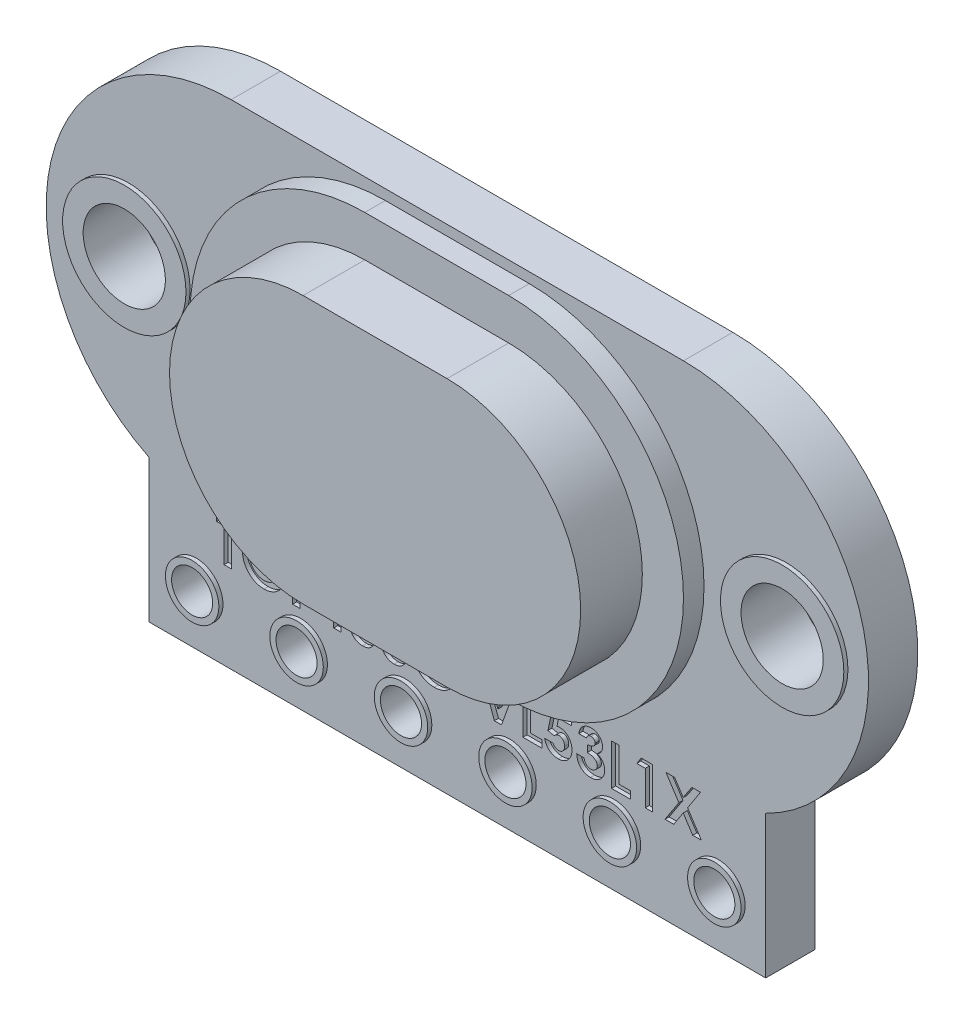
SolidWorks part; units mm, degrees
ref_plane "Plan de face" through (0, 0, 0) normal (0, 0, 1) x (1, 0, 0)
ref_plane "Plan de dessus" through (0, 0, 0) normal (0, 1, 0) x (1, 0, 0)
ref_plane "Plan de droite" through (0, 0, 0) normal (1, 0, 0) x (0, 0, -1)
sketch "Esquisse1" plane through (0, 0, 0) normal (0, 0, 1) x (1, 0, 0)
  line L0 (-7.5, -4.0311) -> (-7.5, -7.5)
  line L1 (0, 19.431) -> (0, -15.0057) construction
  line L2 (-5.5, 0) -> (5.5, 0) construction
  line L5 (-7.5, -7.5) -> (7.5, -7.5)
  line L6 (7.5, -4.0311) -> (7.5, -7.5)
  line L7 (-6.35, -6.23) -> (-3.81, -6.23) construction
  line L8 (-5.5, 4.5) -> (5.5, 4.5)
  circle A2 centre (-8, 0) radius 1
  circle A3 centre (8, 0) radius 1
  circle A4 centre (-6.35, -6.23) radius 0.5
  circle A5 centre (-3.81, -6.23) radius 0.5
  circle A6 centre (-1.27, -6.23) radius 0.5
  circle A7 centre (1.27, -6.23) radius 0.5
  circle A8 centre (3.81, -6.23) radius 0.5
  circle A9 centre (6.35, -6.23) radius 0.5
  arc A10 (-5.5, 4.5) -> (-7.5, -4.0311) centre (-5.5, 0) ccw
  arc A11 (7.5, -4.0311) -> (5.5, 4.5) centre (5.5, 0) ccw
  point P7 (0, 0)
  point P8 (0, 0)
  dimension "D1" = 20
  dimension "D3" = 2
  dimension "D6" = 1
  dimension "D2" = 16
  dimension "D5" = 4.5
  dimension "D4" = 15
  dimension "D8" = 2.54
  dimension "D9" = 1.27
  dimension "D10" = 12
  dimension "D11" = 8.5311
  dimension "D7" = 6
extrude "Boss.-Extru.1" add sketch "Esquisse1" along normal mid plane 1.2
sketch "Esquisse2" plane through (0, 0, 0.6) normal (0, 0, 1) x (1, 0, 0)
  line L0 (-1.75, 0) -> (1.75, 0) construction
  line L1 (-1.75, 4.25) -> (1.75, 4.25)
  line L2 (-1.75, -4.25) -> (1.75, -4.25)
  arc A0 (-1.75, 4.25) -> (-1.75, -4.25) centre (-1.75, 0) ccw
  arc A1 (1.75, -4.25) -> (1.75, 4.25) centre (1.75, 0) ccw
  point P3 (0, 0)
  dimension "D2" = 12
  dimension "D1" = 8.5
extrude "Boss.-Extru.2" add sketch "Esquisse2" along normal blind 0.5
sketch "Esquisse4" plane through (0, 0, 1.1) normal (0, 0, 1) x (1, 0, 0)
  line L4 (-1.75, -3.25) -> (1.75, -3.25)
  line L5 (1.75, 3.25) -> (-1.75, 3.25)
  line L6 (-1.75, -3.25) -> (1.75, -3.25)
  line L7 (1.75, 3.25) -> (-1.75, 3.25)
  arc A4 (-1.75, 3.25) -> (-1.75, -3.25) centre (-1.75, 0) ccw
  arc A5 (1.75, -3.25) -> (1.75, 3.25) centre (1.75, 0) ccw
  arc A6 (-1.75, 3.25) -> (-1.75, -3.25) centre (-1.75, 0) ccw
  arc A7 (1.75, -3.25) -> (1.75, 3.25) centre (1.75, 0) ccw
  dimension "D1" = 1
extrude "Boss.-Extru.4" add sketch "Esquisse4" along normal blind 1.5
sketch "Esquisse3" plane through (0, 0, 0.6) normal (0, 0, 1) x (1, 0, 0)
  line L0 (-6.35, -6.23) -> (-3.81, -6.23) construction
  circle A0 centre (-8, 0) radius 1.5
  circle A1 centre (8, 0) radius 1.5
  circle A2 centre (8, 0) radius 1 construction
  circle A3 centre (-8, 0) radius 1 construction
  circle A4 centre (8, 0) radius 1
  circle A5 centre (-8, 0) radius 1
  circle A6 centre (-6.35, -6.23) radius 0.65
  circle A7 centre (-6.35, -6.23) radius 0.5 construction
  circle A8 centre (-3.81, -6.23) radius 0.65
  circle A9 centre (-1.27, -6.23) radius 0.65
  circle A10 centre (1.27, -6.23) radius 0.65
  circle A11 centre (3.81, -6.23) radius 0.65
  circle A12 centre (6.35, -6.23) radius 0.65
  circle A13 centre (6.35, -6.23) radius 0.5 construction
  circle A14 centre (3.81, -6.23) radius 0.5 construction
  circle A15 centre (1.27, -6.23) radius 0.5 construction
  circle A16 centre (-1.27, -6.23) radius 0.5 construction
  circle A17 centre (-3.81, -6.23) radius 0.5 construction
  circle A18 centre (6.35, -6.23) radius 0.5
  circle A19 centre (3.81, -6.23) radius 0.5
  circle A20 centre (1.27, -6.23) radius 0.5
  circle A21 centre (-1.27, -6.23) radius 0.5
  circle A22 centre (-3.81, -6.23) radius 0.5
  circle A23 centre (-6.35, -6.23) radius 0.5
  dimension "D1" = 3
  dimension "D2" = 1.3
  dimension "D4" = 2.54
  dimension "D3" = 6
extrude "Boss.-Extru.3" add sketch "Esquisse3" along normal blind 0.1
sketch "Esquisse5" plane through (0, 0, 0.6) normal (0, 0, 1) x (1, 0, 0)
  line L0 (-7.5, -5.3812) -> (7.5, -5.3812) construction
  line L1 (-7.5, -4.0311) -> (-7.5, -7.5) construction
  line L2 (7.5, -7.5) -> (7.5, -4.0311) construction
  text T0 "<b>TOF400C-VL53L1X</b>" font "Century Gothic" height 1
extrude "Enlèv. mat.-Extru.1" cut sketch "Esquisse5" against normal blind 0.1
mirror "Symétrie1" about plane through (0, 0, 0) normal (0, 0, 1) of "Boss.-Extru.3"
sketch "Esquisse6" plane through (0, 0, -0.6) normal (0, 0, -1) x (-1, 0, 0)
  line L0 (-5.5521, -5.2944) -> (-5.5521, 1.9609) construction
  text T0 "<b>VIN</b>\r\n<b>GND</b>\r\n<b>SDA</b>\r\n<b>SCL</b>\r\n<b>INT</b>\r\n<b>SHUT</b>" font "Century Gothic" height 1.46
extrude "Enlèv. mat.-Extru.2" cut sketch "Esquisse6" against normal blind 0.1
sketch "Esquisse7" plane through (0, 0, -0.6) normal (0, 0, -1) x (-1, 0, 0)
  line L0 (-7.62, -5.16) -> (-7.42, -4.96)
  line L1 (-7.42, -7.5) -> (-5.28, -7.5)
  line L2 (-7.62, -7.3) -> (-7.62, -5.16)
  line L3 (-7.42, -4.96) -> (-5.28, -4.96)
  line L4 (-5.08, -7.3) -> (-5.08, -5.16)
  line L5 (-7.62, -7.5) -> (-5.08, -4.96) construction
  line L6 (-7.62, -4.96) -> (-5.08, -7.5) construction
  line L7 (-5.28, -4.96) -> (-5.08, -5.16)
  line L8 (-5.28, -7.5) -> (-5.08, -7.3)
  line L9 (-7.62, -7.3) -> (-7.42, -7.5)
  point P0 (-6.35, -6.23)
  dimension "D1" = 2.54
extrude "Boss.-Extru.5" [suppressed] add sketch "Esquisse7" along normal blind 2.5
ref_plane "Plan1" [suppressed] through (6.35, 0, 0) normal (1, 0, 0) x (0, 0, -1)
sketch "Esquisse8" [suppressed] plane through (6.35, 0, 0) normal (1, 0, 0) x (0, 0, -1)
  line L0 (-0.9, -6.23) -> (3.1, -6.23)
  line L1 (4.6, -7.73) -> (4.6, -13.73)
  line L2 (3.1, -4.96) -> (0.6, -4.96) construction
  line L3 (3.1, -7.5) -> (0.6, -7.5) construction
  line L4 (3.1, -5.16) -> (3.1, -7.3) construction
  arc A0 (3.1, -6.23) -> (4.6, -7.73) centre (3.1, -7.73) cw
  dimension "D3" = 4
  dimension "D1" = 7.5
  dimension "D2" = 6
ref_plane "Plan2" [suppressed] through (6.35, -13.73, -4.6) normal (0, -1, 0) x (-1, 0, 0)
sketch "Esquisse9" [suppressed] plane through (6.35, -13.73, -4.6) normal (0, -1, 0) x (-1, 0, 0)
  line L1 (0.32, -0.32) -> (-0.32, -0.32)
  line L2 (0.32, -0.32) -> (0.32, 0.32)
  line L3 (0.32, 0.32) -> (-0.32, 0.32)
  line L4 (-0.32, -0.32) -> (-0.32, 0.32)
  line L5 (0.32, -0.32) -> (-0.32, 0.32) construction
  line L6 (0.32, 0.32) -> (-0.32, -0.32) construction
  point P0 (0, 0)
  dimension "D1" = 0.64
sweep "Balayage1" [suppressed] add profiles "Esquisse9" path "Esquisse8"
chamfer "Chanfrein1" [suppressed] distance 0.2 angle 45
pattern_linear "Répétition linéaire2" [suppressed] count 6 spacing 2.54
